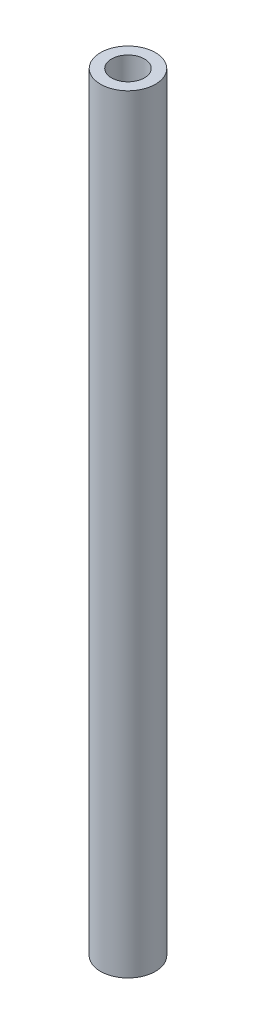
SolidWorks part; units mm, degrees
material "1060 合金"
ref_plane "前视基准面" through (0, 0, 0) normal (0, 0, 1) x (1, 0, 0)
ref_plane "上视基准面" through (0, 0, 0) normal (0, 1, 0) x (1, 0, 0)
ref_plane "右视基准面" through (0, 0, 0) normal (1, 0, 0) x (0, 0, -1)
other "Configuration Table"
sketch "草图1" plane through (0, 0, 0) normal (0, 1, 0) x (1, 0, 0)
  circle A0 centre (0, 0) radius 2.5
  circle A1 centre (0, 0) radius 1.5
  dimension "D1" = 3
  dimension "5" = 5
extrude "凸台-拉伸1" add sketch "草图1" along normal blind 70
